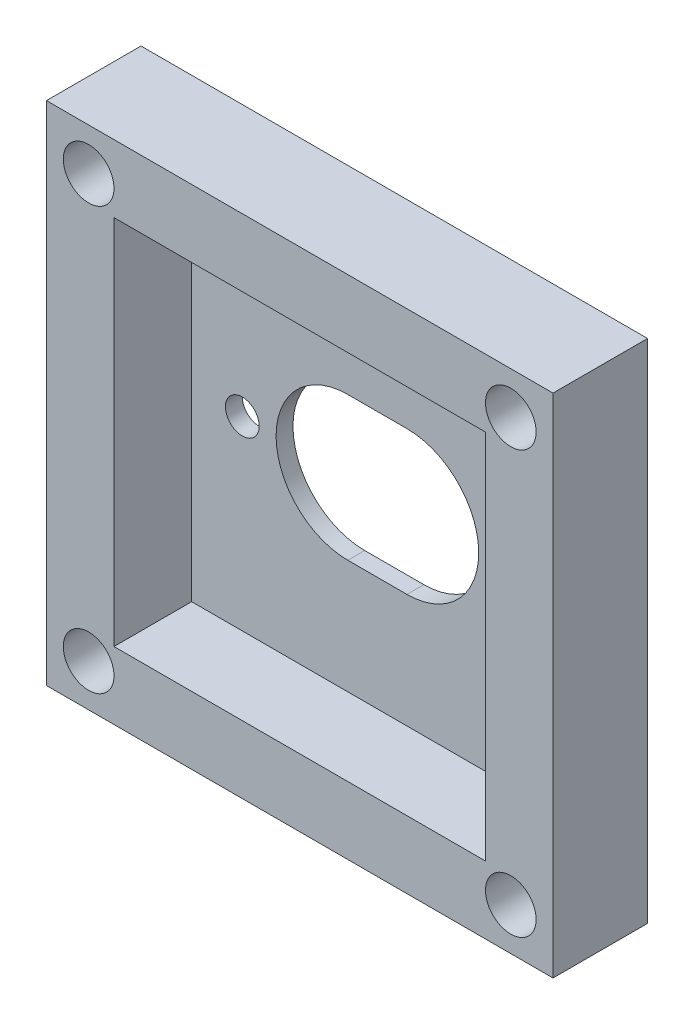
SolidWorks part; units mm, degrees
ref_plane "Plan de face" through (0, 0, 0) normal (0, 0, 1) x (1, 0, 0)
ref_plane "Plan de dessus" through (0, 0, 0) normal (0, 1, 0) x (1, 0, 0)
ref_plane "Plan de droite" through (0, 0, 0) normal (1, 0, 0) x (0, 0, -1)
sketch "Croquis1" plane through (0, 0, 0) normal (0, 0, 1) x (1, 0, 0)
  line L0 (-1.75, 4.25) -> (1.75, 4.25)
  line L1 (-15, 15) -> (15, 15)
  line L2 (-15, 15) -> (-15, -15)
  line L3 (-15, -15) -> (15, -15)
  line L4 (15, 15) -> (15, -15)
  line L5 (1.75, -4.25) -> (-1.75, -4.25)
  arc A0 (-1.75, 4.25) -> (-1.75, -4.25) centre (-1.75, 0) ccw
  arc A1 (1.75, -4.25) -> (1.75, 4.25) centre (1.75, 0) ccw
  circle A2 centre (-8, 0) radius 1
  circle A3 centre (8, 0) radius 1
  dimension "D1" = 4.25
  dimension "D2" = 2
  dimension "D3" = 4.25
  dimension "D5" = 2
  dimension "D4" = 3.5
  dimension "D6" = 30
  dimension "D7" = 30
extrude "Saliente-Extruir2" add sketch "Croquis1" against normal blind 1
sketch "Croquis2" plane through (0, 0, 0) normal (0, 0, 1) x (1, 0, 0)
  line L1 (-15, 15) -> (15, 15)
  line L2 (-15, 15) -> (-15, -15)
  line L3 (-15, -15) -> (15, -15)
  line L4 (15, 15) -> (15, -15)
  line L5 (-11, 11) -> (11, 11)
  line L6 (-11, 11) -> (-11, -11)
  line L7 (-11, -11) -> (11, -11)
  line L8 (11, 11) -> (11, -11)
  dimension "D1" = 4
  dimension "D2" = 4
  dimension "D3" = 4
  dimension "D4" = 4
extrude "Saliente-Extruir3" add sketch "Croquis2" along normal blind 10
sketch "Croquis4" plane through (0, 0, 10) normal (0, 0, 1) x (1, 0, 0)
  line L0 (15, 15) -> (-15, 15) construction
  line L1 (-15, 15) -> (-15, -15) construction
  line L2 (0, 15) -> (0, -15) construction
  line L3 (-15, -15) -> (15, -15) construction
  line L4 (-15, 0) -> (15, 0) construction
  line L5 (15, -15) -> (15, 15) construction
  circle A0 centre (-12.5, 12.5) radius 1.5
  circle A1 centre (12.5, 12.5) radius 1.5
  circle A2 centre (12.5, -12.5) radius 1.5
  circle A3 centre (-12.5, -12.5) radius 1.5
  dimension "D1" = 3
  dimension "D2" = 2.5
  dimension "D3" = 2.5
extrude "Cortar-Extruir2" cut sketch "Croquis4" against normal blind 44
sketch "Croquis5" plane through (-15, 0, 0) normal (-1, 0, 0) x (0, 0, 1)
  line L1 (-1, 15) -> (10, 15) construction
  line L2 (4.6, 15) -> (4.6, -15)
  line L3 (-1, -15) -> (10, -15) construction
  line L7 (10, -15) -> (4.6, -15)
  line L8 (10, -15) -> (10, 15)
  line L9 (10, 15) -> (4.6, 15)
extrude "Cortar-Extruir3" cut sketch "Croquis5" against normal blind 46
